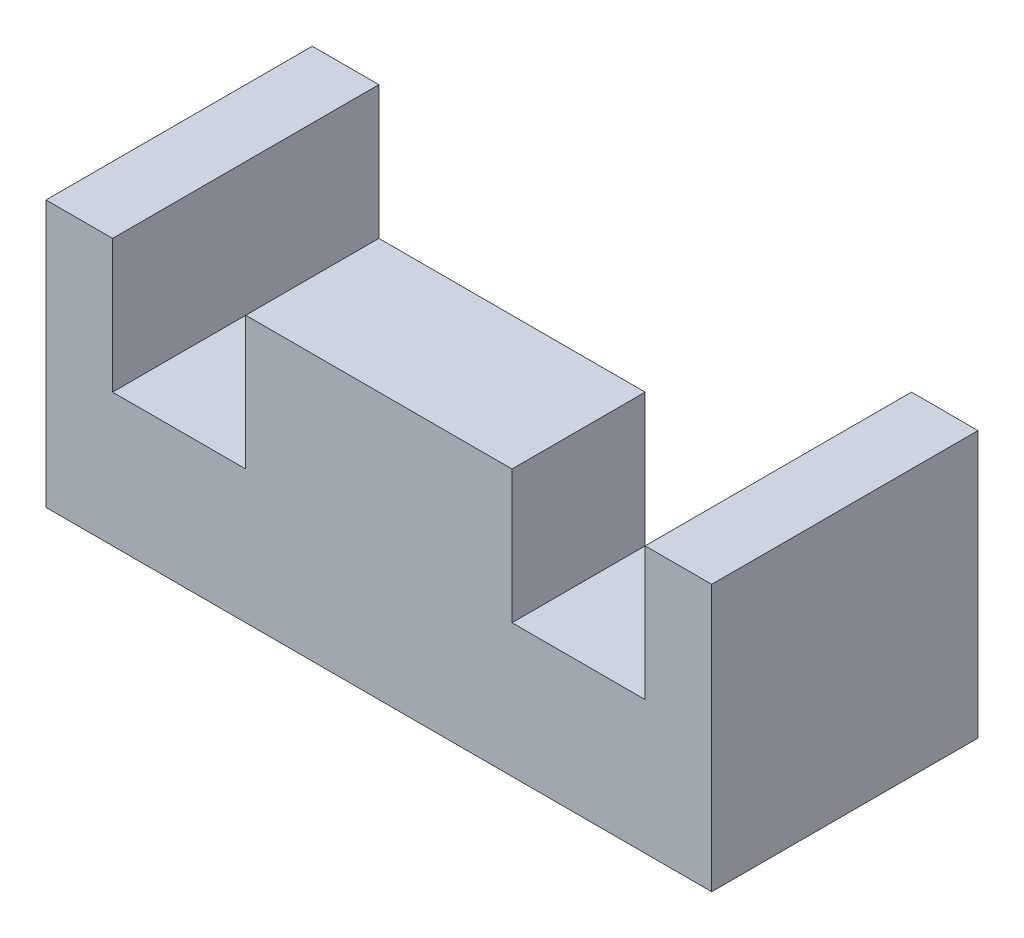
SolidWorks part; units mm, degrees
ref_plane "前基準面" through (0, 0, 0) normal (0, 0, 1) x (1, 0, 0)
ref_plane "上基準面" through (0, 0, 0) normal (0, 1, 0) x (1, 0, 0)
ref_plane "右基準面" through (0, 0, 0) normal (1, 0, 0) x (0, 0, -1)
sketch "草圖1" plane through (0, 0, 0) normal (0, 0, 1) x (1, 0, 0)
  line L1 (-25, 10) -> (25, 10)
  line L2 (-25, 10) -> (-25, -10)
  line L3 (-25, -10) -> (25, -10)
  line L4 (25, 10) -> (25, -10)
  line L5 (-25, 10) -> (25, -10) construction
  line L6 (-25, -10) -> (25, 10) construction
  line L7 (-20, 10) -> (-10, 10)
  line L8 (-20, 10) -> (-20, 0)
  line L9 (-20, 0) -> (-10, 0)
  line L10 (-10, 10) -> (-10, 0)
  line L11 (10, 10) -> (20, 10)
  line L12 (10, 10) -> (10, 0)
  line L13 (10, 0) -> (20, 0)
  line L14 (20, 10) -> (20, 0)
  point P0 (0, 0)
  point P16 (-28.2832, 10.3938)
  dimension "D1" = 50
  dimension "D2" = 20
  dimension "D3" = 5
  dimension "D4" = 5
  dimension "D5" = 10
  dimension "D6" = 10
  dimension "D7" = 10
  dimension "D8" = 10
extrude "填料-伸長1" add sketch "草圖1" along normal blind 20 contours L1 L14 L13 L12 L10 L9 L8 L2 L3 L4
sketch "草圖2" plane through (0, 0, 0) normal (0, 0, -1) x (-1, 0, 0)
  line L0 (25, -10) -> (-25, -10) construction
  line L1 (10, 10) -> (-10, 10)
  line L2 (10, 10) -> (10, -10)
  line L3 (10, -10) -> (-10, -10)
  line L4 (-10, 10) -> (-10, -10)
extrude "除料-伸長1" cut sketch "草圖2" against normal blind 10
